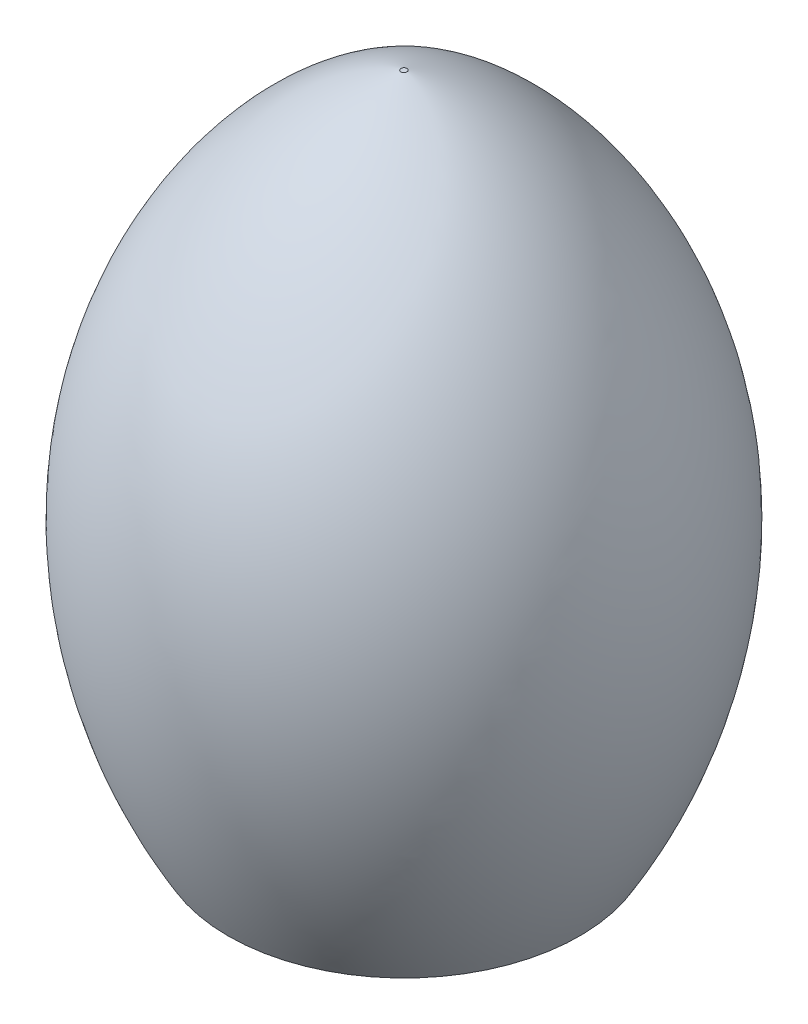
SolidWorks part; units mm, degrees
ref_plane "Front Plane" through (0, 0, 0) normal (0, 0, 1) x (1, 0, 0)
ref_plane "Top Plane" through (0, 0, 0) normal (0, 1, 0) x (1, 0, 0)
ref_plane "Right Plane" through (0, 0, 0) normal (1, 0, 0) x (0, 0, -1)
sketch "Sketch3" plane through (0, -67.0312, 0) normal (1, 0, 0) x (0, 0, -1)
  line L0 (0, -86.409) -> (45.0343, -86.409)
  line L1 (-1.7336, -89.409) -> (45.0343, -89.409)
  line L2 (45.0343, 83.8246) -> (45.0343, 86.7153)
  line L3 (45.0343, 86.7153) -> (44.232, 86.7153)
  line L4 (45.0343, -86.409) -> (45.0343, -89.409)
  line L5 (45.0343, 83.8246) -> (45.0343, -86.409)
  spline S0 degree 3 poles (0, -86.409) (-19.811, -52.0343) (-30.029, 18.5668) (19.0108, 76.6016) (45.0343, 83.8246) knots 0 0 0 0 0.591831 1 1 1 1
  spline S1 degree 1 poles (-1.7336, -89.409) (44.232, 86.7153) knots 0 0 1 1 construction
  spline S2 degree 3 poles (-1.7336, -89.409) (-1.9974, -88.9513) (-2.5217, -88.0438) (-3.5962, -86.1662) (-5.4085, -82.8673) (-8.8314, -76.153) (-13.0915, -66.2897) (-17.156, -54.0931) (-21.1045, -37.4673) (-23.1522, -16.2151) (-20.9858, 5.0892) (-16.5139, 21.7952) (-10.1294, 38.1803) (-0.9179, 53.6673) (10.8076, 66.9789) (20.7951, 75.5554) (30.0609, 81.2504) (37.9888, 84.7558) (42.135, 86.1332) (44.232, 86.7153) knots -0.00862 -0.00862 -0.00862 -0.00862 -0.00074 0.00714 0.022899 0.054419 0.117458 0.180496 0.243535 0.369613 0.49569 0.558729 0.621768 0.747845 0.810884 0.873923 0.936961 0.968481 1 1 1 1
  dimension "D1" = 3
revolve "Revolve2" add sketch "Sketch3" angle 360 about L5
sketch "Sketch6" plane through (0, -156.4402, 0) normal (0, -1, 0) x (1, 0, 0)
  circle A1 centre (0, -45.0343) radius 46.7679
